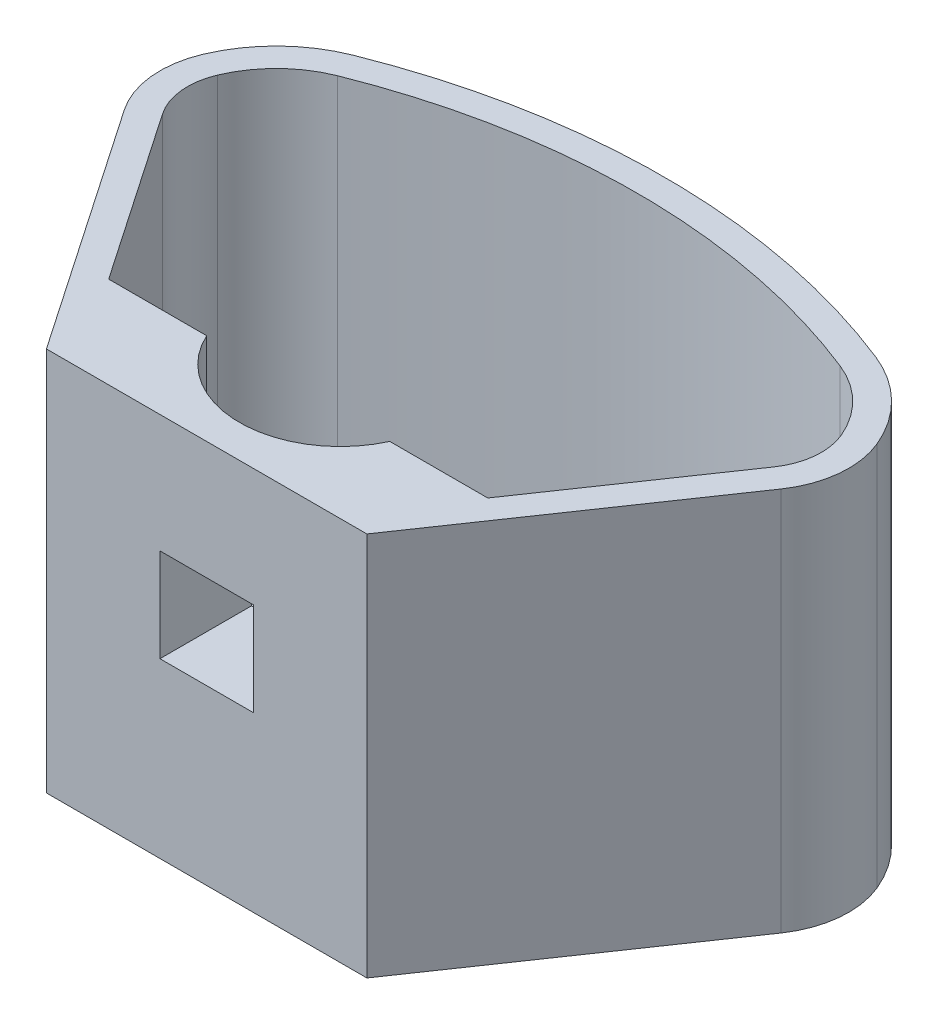
SolidWorks part; units mm, degrees
ref_plane "Спереди" through (0, 0, 0) normal (0, 0, 1) x (1, 0, 0)
ref_plane "Сверху" through (0, 0, 0) normal (0, 1, 0) x (1, 0, 0)
ref_plane "Справа" through (0, 0, 0) normal (1, 0, 0) x (0, 0, -1)
sketch "Sketch1" plane through (0, 0, 0) normal (0, 1, 0) x (1, 0, 0)
  line L0 (17.5, 0) -> (-17.5, 0)
  line L1 (0, 0) -> (0, 50) construction
  line L2 (38, 50) -> (-38, 50) construction
  line L3 (-38, 30) -> (38, 30) construction
  line L4 (-38, 30) -> (-17.5, 0)
  line L5 (17.5, 0) -> (38, 30)
  line L6 (-38, 30) -> (-38, 40)
  line L7 (38, 30) -> (38, 40)
  arc A0 (-38, 40) -> (38, 40) centre (0, -27.2) cw
  point P4 (0, 0)
  point P9 (0, 50)
  dimension "D1" = 35
  dimension "D2" = 50
  dimension "D3" = 76
  dimension "D4" = 20
  dimension "D5" = 10
extrude "Boss-Extrude1" add sketch "Sketch1" along normal blind 42
fillet "Fillet3" radius 15 2 edges at (38, 21, -40) (-38, 21, -40)
fillet "Fillet4" radius 10 2 edges at (38, 21, -30) (-38, 21, -30)
shell "Shell1" thickness 3
sketch "Sketch3" plane through (0, 42, 0) normal (0, 1, 0) x (1, 0, 0)
  line L0 (-20.6998, 10) -> (20.6998, 10)
  line L1 (-33.3915, 28.5732) -> (-15.9165, 3) construction
  line L2 (15.9165, 3) -> (33.3915, 28.5732) construction
  line L3 (20.6998, 10) -> (15.9165, 3)
  line L4 (15.9165, 3) -> (-15.9165, 3)
  line L5 (-15.9165, 3) -> (-20.6998, 10)
  dimension "D1" = 7
extrude "Boss-Extrude2" add sketch "Sketch3" against normal up to surface (39 mm away) up to face at (0, 3, -27.938)
sketch "Sketch4" plane through (0, 0, 0) normal (0, 0, 1) x (1, 0, 0)
  line L0 (0, 42) -> (0, 0) construction
  line L1 (-17.5, 42) -> (17.5, 42) construction
  line L3 (5.1, 18.9) -> (-5.1, 18.9)
  line L4 (5.1, 18.9) -> (5.1, 29.1)
  line L5 (5.1, 29.1) -> (-5.1, 29.1)
  line L6 (-5.1, 18.9) -> (-5.1, 29.1)
  line L7 (5.1, 18.9) -> (-5.1, 29.1) construction
  line L8 (5.1, 29.1) -> (-5.1, 18.9) construction
  point P5 (0, 24)
  point P10 (0, 21)
  dimension "D1" = 3
  dimension "D2" = 10.2
extrude "Cut-Extrude1" cut sketch "Sketch4" against normal up to next
sketch "Sketch5" plane through (0, 42, 0) normal (0, 1, 0) x (1, 0, 0)
  line L0 (20.6998, 10) -> (-20.6998, 10) construction
  line L1 (0, 0) -> (0, 10) construction
  line L2 (-17.5, 0) -> (17.5, 0) construction
  line L3 (-10, 10) -> (10, 10)
  arc A0 (-10, 10) -> (10, 10) centre (0, 14.5826) ccw
  point P9 (0, 10)
  dimension "D1" = 11
  dimension "D2" = 20
extrude "Cut-Extrude2" cut sketch "Sketch5" against normal blind 10
